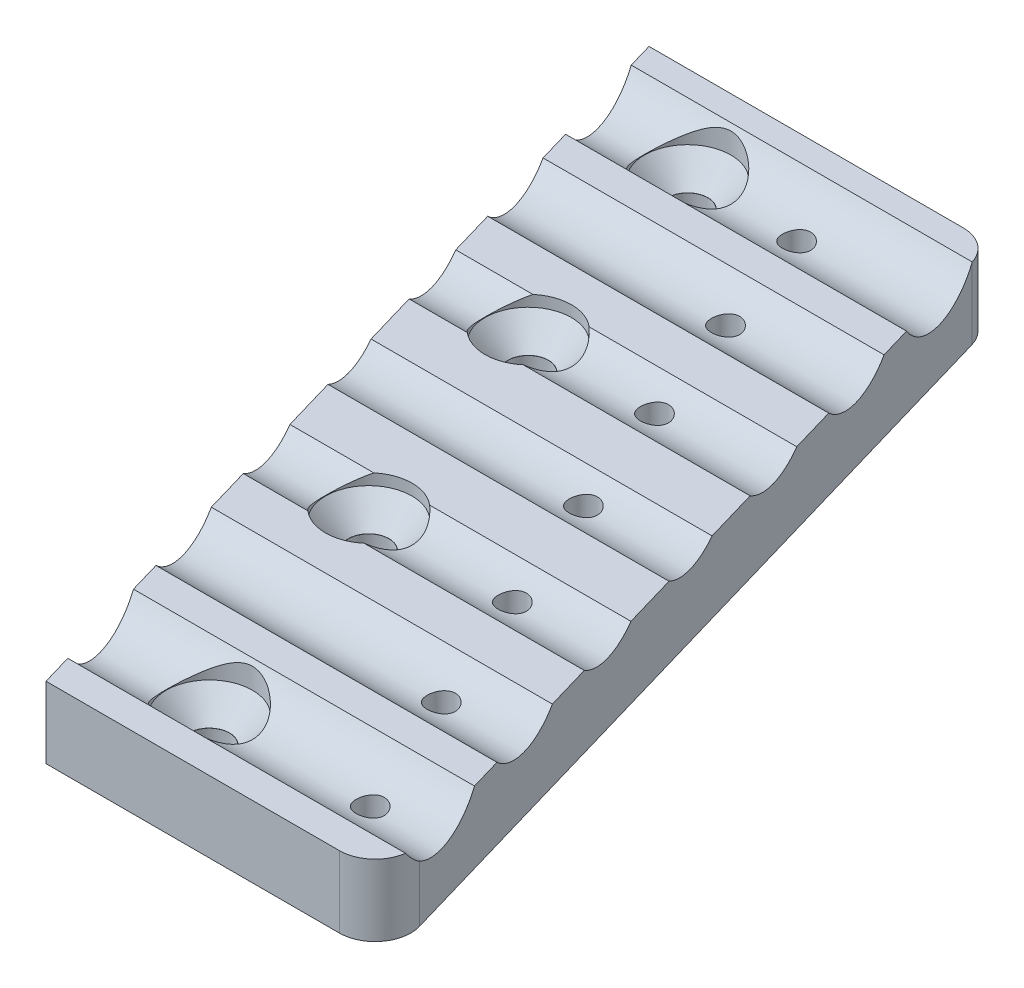
SolidWorks part; units mm, degrees
ref_plane "Front Plane" through (0, 0, 0) normal (0, 0, 1) x (1, 0, 0)
ref_plane "Top Plane" through (0, 0, 0) normal (0, 1, 0) x (1, 0, 0)
ref_plane "Right Plane" through (0, 0, 0) normal (1, 0, 0) x (0, 0, -1)
sketch "Sketch1" plane through (0, 0, 0) normal (0, 1, 0) x (1, 0, 0)
  line L0 (241.3333, 1024) -> (1206.6667, 1024) construction
sketch "Sketch2" [suppressed] plane through (0, 0, 0) normal (0, 1, 0) x (1, 0, 0)
  line L0 (742.1534, 1793.839) -> (907.6642, 1225.9649)
  line L1 (596.8442, 1766.8638) -> (750.0155, 1766.8638)
  line L2 (596.8442, 1241.63) -> (903.0985, 1241.63)
  line L3 (596.8442, 1766.8638) -> (596.8442, 1241.63)
  line L4 (485.775, 863.6) -> (485.775, 819.15)
sketch "Sketch3" plane through (0, 0, 0) normal (0, 1, 0) x (1, 0, 0)
  line L0 (30.988, 73.406) -> (51.2128, 4.064)
  line L1 (22.0768, 0) -> (48.1648, 0)
  line L3 (42.9985, 4.9766) -> (23.1226, 73.1226) construction
  line L4 (0, 75.692) -> (27.94, 75.692)
  line L5 (0, 75.692) -> (22.0768, 0)
  arc A0 (30.988, 73.406) -> (27.94, 75.692) centre (27.94, 72.517) ccw
  arc A1 (48.1648, 0) -> (51.2128, 4.064) centre (48.1648, 3.175) ccw
  dimension "D1" = 3.175
  dimension "D2" = 3.175
sketch "Sketch4" plane through (0, 0, 0) normal (0, 1, 0) x (1, 0, 0)
  line L0 (0, 6.858) -> (76.2, 6.858)
  line L2 (0, 27.686) -> (76.2, 27.686)
  line L3 (0, 48.514) -> (76.2, 48.514)
  line L4 (0, 38.1) -> (76.2, 38.1)
  line L5 (0, 17.272) -> (76.2, 17.272)
  line L6 (0, 58.928) -> (76.2, 58.928)
  line L7 (0, 69.342) -> (76.2, 69.342)
sketch "Sketch5" plane through (0, 0, 0) normal (1, 0, 0) x (0, 0, -1)
  circle A0 centre (38.1, -351.3938) radius 355.6
sketch "Sketch6" plane through (0, 0, 0) normal (1, 0, 0) x (0, 0, -1)
  line L0 (69.342, 0) -> (69.342, -12.7)
  line L1 (58.928, 0) -> (58.928, -12.7)
  line L2 (48.514, 0) -> (48.514, -12.7)
  line L3 (38.1, 0) -> (38.1, -12.7)
  line L4 (27.686, 0) -> (27.686, -12.7)
  line L5 (17.272, 0) -> (17.272, -12.7)
  line L6 (6.858, 0) -> (6.858, -12.2272)
  line L7 (6.858, 0) -> (6.858, 11.1603)
  line L8 (17.272, 0) -> (17.272, 13.7279)
  line L9 (27.686, 0) -> (27.686, 14.1996)
  line L10 (38.1, 0) -> (38.1, 14.6712)
  line L11 (48.514, 0) -> (48.514, 13.7279)
  line L12 (58.928, 0) -> (58.928, 13.7279)
  line L13 (69.342, 0) -> (69.342, 12.6275)
sketch "Sketch7" plane through (0, 0, 0) normal (1, 0, 0) x (0, 0, -1)
  circle A0 centre (6.8579, 2.8312) radius 5
  circle A1 centre (38.1, -351.3938) radius 355.6 construction
  circle A2 centre (17.2793, 3.5962) radius 5
  circle A3 centre (27.6919, 4.0539) radius 5
  circle A4 centre (38.1, 4.2062) radius 5
  circle A5 centre (48.5081, 4.0539) radius 5
  circle A6 centre (58.9207, 3.5962) radius 5
  circle A7 centre (69.3421, 2.8312) radius 5
extrude "Boss-Extrude2" add sketch "Sketch3" against normal blind 6.35
sketch "Sketch21" plane through (0, 0, 0) normal (0, 1, 0) x (1, 0, 0)
  line L0 (0, 69.342) -> (76.2, 69.342) construction
  line L1 (19.4733, 69.342) -> (51.4722, -12.0387) construction
  line L2 (0, 58.928) -> (76.2, 58.928) construction
  line L3 (0, 48.514) -> (76.2, 48.514) construction
  line L4 (0, 38.1) -> (76.2, 38.1) construction
  line L5 (0, 27.686) -> (76.2, 27.686) construction
  line L6 (0, 17.272) -> (76.2, 17.272) construction
  line L7 (0, 6.858) -> (76.2, 6.858) construction
  line L8 (51.2128, 4.064) -> (30.988, 73.406) construction
  circle A0 centre (19.4733, 69.342) radius 1.25
  circle A1 centre (23.5681, 58.928) radius 1.25
  circle A2 centre (27.6629, 48.514) radius 1.25
  circle A3 centre (31.7577, 38.1) radius 1.25
  circle A4 centre (35.8525, 27.686) radius 1.25
  circle A5 centre (39.9473, 17.272) radius 1.25
  circle A6 centre (44.042, 6.858) radius 1.25
  point P0 (19.4733, 69.342)
  point P5 (23.5681, 58.928)
  point P7 (27.6629, 48.514)
  point P10 (31.7577, 38.1)
  point P13 (35.8525, 27.686)
  point P16 (39.9473, 17.272)
  point P19 (44.042, 6.858)
  point P43 (32.1733, 69.342)
  dimension "D2" = 2.5
  dimension "D1" = 12.7
sketch "Sketch22" plane through (0, 0, 0) normal (0, 1, 0) x (1, 0, 0)
  line L0 (9.7896, 69.342) -> (35.0623, -9.8154) construction
  line L1 (0, 69.342) -> (76.2, 69.342) construction
  line L2 (0, 75.692) -> (22.0768, 0) construction
  line L3 (0, 48.514) -> (76.2, 48.514) construction
  line L4 (0, 27.686) -> (76.2, 27.686) construction
  line L5 (0, 6.858) -> (76.2, 6.858) construction
  circle A0 centre (9.7896, 69.342) radius 1.7907
  circle A1 centre (16.4394, 48.514) radius 1.7907
  circle A2 centre (23.0892, 27.686) radius 1.7907
  circle A3 centre (29.739, 6.858) radius 1.7907
  point P4 (1.8521, 69.342)
  dimension "D1" = 3.5814
ref_plane "Plane1" through (9.7896, 0, 0) normal (1, 0, 0) x (0, 0, -1)
ref_plane "Plane2" through (16.4394, 0, 0) normal (1, 0, 0) x (0, 0, -1)
ref_plane "Plane3" through (23.0892, 0, 0) normal (1, 0, 0) x (0, 0, -1)
ref_plane "Plane4" through (29.739, 0, 0) normal (1, 0, 0) x (0, 0, -1)
sketch "Sketch24" plane through (9.7896, 0, 0) normal (1, 0, 0) x (0, 0, -1)
  line L1 (69.342, 1.5949) -> (69.342, -2.1688)
  line L6 (69.342, -2.1688) -> (69.342, -4.4802)
  line L8 (38.1, 14.6712) -> (38.1, -12.7) construction
  line L15 (69.342, 0) -> (69.342, -12.7) construction
  line L16 (69.342, -4.4802) -> (71.1454, -4.4802)
  line L17 (71.1454, -4.4802) -> (73.1849, -2.2151)
  line L18 (73.1849, -2.2151) -> (73.1849, 1.5949)
  line L19 (73.1849, 1.5949) -> (69.342, 1.5949)
  line L20 (69.342, 0) -> (69.342, 12.6275) construction
  circle A1 centre (69.3421, 2.8312) radius 5 construction
sketch "Sketch26" plane through (16.4394, 0, 0) normal (1, 0, 0) x (0, 0, -1)
  line L0 (48.514, -0.9461) -> (48.514, -3.2575)
  line L2 (48.514, -3.2575) -> (50.3174, -3.2575)
  line L3 (50.3174, -3.2575) -> (52.3569, -0.9924)
  line L4 (52.3569, -0.9924) -> (52.3569, 3.0579)
  line L5 (52.3569, 3.0579) -> (48.514, 3.0579)
  line L7 (48.514, 3.0579) -> (48.514, -0.9461)
  line L8 (38.1, 14.6712) -> (38.1, -12.7) construction
sketch "Sketch28" plane through (23.0892, 0, 0) normal (1, 0, 0) x (0, 0, -1)
  line L8 (38.1, 14.6712) -> (38.1, -12.7) construction
  line L9 (27.686, 3.0579) -> (27.686, -0.9461)
  line L10 (23.8431, 3.0579) -> (27.686, 3.0579)
  line L11 (23.8431, -0.9924) -> (23.8431, 3.0579)
  line L12 (25.8826, -3.2575) -> (23.8431, -0.9924)
  line L13 (27.686, -3.2575) -> (25.8826, -3.2575)
  line L14 (27.686, -0.9461) -> (27.686, -3.2575)
sketch "Sketch29" plane through (29.739, 0, 0) normal (1, 0, 0) x (0, 0, -1)
  line L0 (3.0151, 1.5949) -> (6.858, 1.5949)
  line L2 (3.0151, -2.2151) -> (3.0151, 1.5949)
  line L3 (5.0546, -4.4802) -> (3.0151, -2.2151)
  line L4 (6.858, -4.4802) -> (5.0546, -4.4802)
  line L5 (6.858, -2.1688) -> (6.858, -4.4802)
  line L7 (6.858, 1.5949) -> (6.858, -2.1688)
  line L8 (38.1, 14.6712) -> (38.1, -12.7) construction
extrude "Cut-Extrude1" cut sketch "Sketch7" along normal blind 74.422
extrude "Cut-Extrude2" cut sketch "Sketch22" against normal blind 74.422
extrude "Cut-Extrude3" cut sketch "Sketch21" against normal blind 74.422
revolve "Cut-Revolve1" cut sketch "Sketch24" angle 360 about L1
revolve "Cut-Revolve2" cut sketch "Sketch26" angle 360 about L7
revolve "Cut-Revolve3" cut sketch "Sketch28" angle 360 about L9
revolve "Cut-Revolve4" cut sketch "Sketch29" angle 360 about L7
